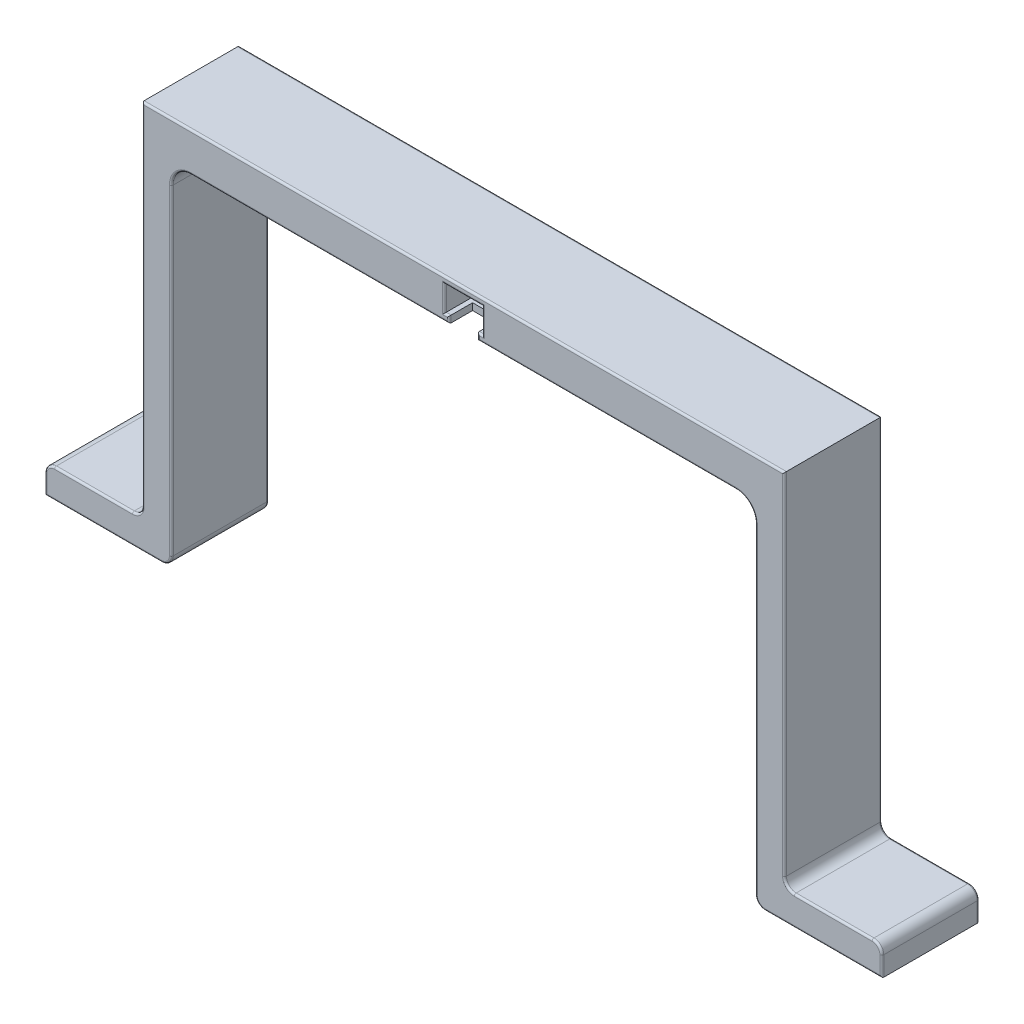
SolidWorks part; units mm, degrees
material "ABS"
ref_plane "Front Plane" through (0, 0, 0) normal (0, 0, 1) x (1, 0, 0)
ref_plane "Top Plane" through (0, 0, 0) normal (0, 1, 0) x (1, 0, 0)
ref_plane "Right Plane" through (0, 0, 0) normal (1, 0, 0) x (0, 0, -1)
sketch "Sketch1" plane through (0, 0, 0) normal (0, 0, 1) x (1, 0, 0)
  line L0 (-215, 0) -> (-150, 0)
  line L1 (-150, 0) -> (-150, 180)
  line L2 (-150, 180) -> (150, 180)
  line L3 (150, 180) -> (150, 0)
  line L4 (150, 0) -> (215, 0)
  line L5 (-215, 15) -> (-165, 15)
  line L6 (-165, 15) -> (-165, 195)
  line L8 (165, 195) -> (165, 15)
  line L9 (165, 15) -> (215, 15)
  line L10 (-215, 15) -> (-215, 0)
  line L11 (215, 15) -> (215, 0)
  line L12 (-165, 195) -> (165, 195) construction
  line L13 (-150, 200) -> (150, 200)
  line L14 (-150, 200) -> (-165, 200)
  line L15 (-165, 200) -> (-165, 195)
  line L16 (150, 200) -> (165, 200)
  line L17 (165, 200) -> (165, 195)
  point P5 (0, 180)
  dimension "D1" = 65
  dimension "D2" = 300
  dimension "D3" = 150
  dimension "D4" = 180
  dimension "D6" = 20
  dimension "D5" = 15
extrude "Boss-Extrude1" add sketch "Sketch1" along normal mid plane 50
sketch "Sketch2" plane through (0, 0, 25) normal (0, 0, 1) x (1, 0, 0)
  line L0 (165, 200) -> (-165, 200) construction
  line L1 (-9.75, 196.5) -> (9.75, 196.5)
  line L2 (-9.75, 196.5) -> (-9.75, 183.5)
  line L3 (-9.75, 183.5) -> (9.75, 183.5)
  line L4 (9.75, 196.5) -> (9.75, 183.5)
  line L5 (-9.75, 196.5) -> (9.75, 183.5) construction
  line L6 (-9.75, 183.5) -> (9.75, 196.5) construction
  point P0 (0, 190)
  dimension "D1" = 19.5
  dimension "D2" = 13
  dimension "D3" = 10
extrude "Cut-Extrude1" cut sketch "Sketch2" against normal through all
sketch "Sketch3" plane through (0, 180, 0) normal (0, -1, 0) x (1, 0, 0)
  line L0 (-150, 25) -> (150, 25) construction
  line L1 (-7.25, 25) -> (7.25, 25)
  line L2 (-7.25, 25) -> (-7.25, 13)
  line L3 (-7.25, -20) -> (7.25, -20)
  line L4 (7.25, 25) -> (7.25, 13)
  line L5 (-7.25, 25) -> (7.25, -20) construction
  line L6 (-7.25, -20) -> (7.25, 25) construction
  line L7 (-7.25, 7) -> (-7.25, -20)
  line L8 (-7.25, 7) -> (7.25, 7)
  line L10 (-7.25, 13) -> (7.25, 13)
  line L12 (-7.25, 7) -> (7.25, 13) construction
  line L13 (-7.25, 13) -> (7.25, 7) construction
  line L14 (7.25, 7) -> (7.25, -20)
  circle A0 centre (0, 10) radius 2.5
  point P4 (0, 2.5)
  dimension "D3" = 5
  dimension "D1" = 45
  dimension "D2" = 14.5
  dimension "D4" = 15
  dimension "D5" = 3
extrude "Cut-Extrude2" cut sketch "Sketch3" against normal blind 5
fillet "Fillet2" radius 10 2 edges at (150, 180, 0) (-150, 180, 0)
fillet "Fillet3" radius 5 6 edges at (150, 0, 0) (-150, 0, 0) (165, 15, 0) (-165, 15, 0) (215, 15, 0) (-215, 15, 0)
fillet "Fillet4" radius 1 52 edges at (147.0711, 177.0711, 25) (-73.625, 180, 25) (73.625, 180, 25) (-147.0711, 177.0711, 25) (-150, 87.5, 25) (-151.4645, 1.4645, 25) (-185, 0, 25) (-215, 5, 25) (-213.5355, 13.5355, 25) (-190, 15, 25) (-166.4645, 16.4645, 25) (-165, 110, 25) (165, 110, 25) (166.4645, 16.4645, 25) (190, 15, 25) (213.5355, 13.5355, 25) (215, 5, 25) (185, 0, 25) (151.4645, 1.4645, 25) (150, 87.5, 25) (215, 5, -25) (213.5355, 13.5355, -25) (190, 15, -25) (166.4645, 16.4645, -25) (165, 110, -25) (-165, 110, -25) (-166.4645, 16.4645, -25) (-190, 15, -25) (-213.5355, 13.5355, -25) (-215, 5, -25) (-185, 0, -25) (-151.4645, 1.4645, -25) (-150, 87.5, -25) (-147.0711, 177.0711, -25) (0, 180, -25) (147.0711, 177.0711, -25) (150, 87.5, -25) (151.4645, 1.4645, -25) (185, 0, -25) (0, 196.5, 25) (-9.75, 190, 25) (-8.5, 183.5, 25) (8.5, 183.5, 25) (9.75, 190, 25) (-9.75, 190, -25) (0, 196.5, -25) (9.75, 190, -25) (0, 183.5, -25) (7.25, 181.75, 25) (-7.25, 181.75, 25) (0, 200, 25) (0, 200, -25)
